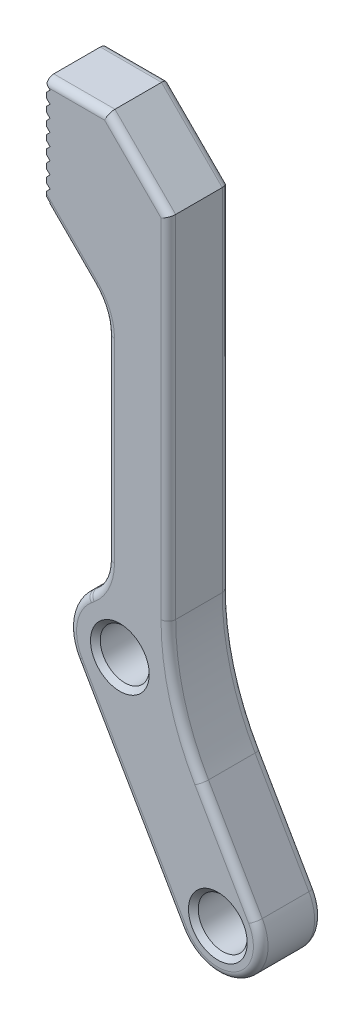
SolidWorks part; units mm, degrees
ref_plane "Ön Düzlem" through (0, 0, 0) normal (0, 0, 1) x (1, 0, 0)
ref_plane "Üst Düzlem" through (0, 0, 0) normal (0, 1, 0) x (1, 0, 0)
ref_plane "Sağ Düzlem" through (0, 0, 0) normal (1, 0, 0) x (0, 0, -1)
sketch "Çizim1" plane through (0, 0, 0) normal (0, 0, 1) x (1, 0, 0)
  line L0 (-37.3964, -419.0951) -> (-37.3964, 583.0751) construction
  line L1 (-37.3964, 12.3964) -> (-12.3964, 12.3964)
  line L2 (-12.3964, 12.3964) -> (12.3964, -12.3964)
  line L3 (12.3964, -12.3964) -> (12.3964, -182.3964)
  line L4 (12.3964, -182.3964) -> (47.7591, -243.6464)
  line L5 (17.4482, -261.1464) -> (-33.7917, -172.3964)
  line L6 (-33.7917, -172.3964) -> (-12.6036, -154.6175)
  line L7 (-12.6036, -154.6175) -> (-12.6036, -57.3964)
  line L8 (-12.6036, -57.3964) -> (-37.3964, -32.6036)
  line L9 (-37.3964, 12.3964) -> (-37.3964, -32.6036)
  line L10 (-37.3964, 10.3964) -> (-35.3964, 8.3964) construction
  line L11 (-35.3964, 8.3964) -> (-37.3964, 6.3964) construction
  arc A0 (17.4482, -261.1464) -> (47.7591, -243.6464) centre (32.6036, -252.3964) ccw
  circle A1 centre (-7.3964, -177.3964) radius 10
  circle A2 centre (32.6036, -252.3964) radius 10
  point P29 (0, 0)
  dimension "D1" = 35
  dimension "D18" = 20
  dimension "D19" = 20
  dimension "D2" = 100
  dimension "D3" = 45
  dimension "D4" = 135
  dimension "D5" = 25
  dimension "D6" = 25
  dimension "D7" = 170
  dimension "D8" = 70
  dimension "D9" = 80
  dimension "D10" = 4
  dimension "D11" = 4
  dimension "D12" = 26.3953
  dimension "D13" = 22.7789
  dimension "D14" = 30
  dimension "D15" = 24.7927
  dimension "D16" = 570.6787
  dimension "D17" = 246.6987
extrude "Yükseklik-Ekstrüzyon1" add sketch "Çizim1" along normal blind 25
fillet "Radyus1" radius 20 3 edges at (-12.6036, -57.3964, 12.5) (-12.6036, -154.6175, 12.5) (-33.7917, -172.3964, 12.5)
fillet "Radyus2" radius 100 1 edges at (12.3964, -182.3964, 12.5)
chamfer "Pah1" distance 2 angle 45 4 edges at (42.6036, -252.3964, 25) (42.6036, -252.3964, 0) (2.6036, -177.3964, 25) (2.6036, -177.3964, 0)
sketch "Çizim2" plane through (0, 0, 0) normal (0, 0, -1) x (-1, 0, 0)
  line L0 (37.3964, 12.3964) -> (37.3964, 10.3964)
  line L1 (37.3964, 12.3964) -> (37.3964, -32.6036) construction
  line L2 (37.3964, 10.3964) -> (35.8964, 8.8964)
  line L3 (35.8964, 8.8964) -> (37.3964, 7.3964)
  line L4 (37.3964, 7.3964) -> (37.3964, 5.3964)
  line L5 (37.3964, 5.3964) -> (35.8964, 3.8964)
  line L6 (35.8964, 3.8964) -> (37.3964, 2.3964)
  line L7 (37.3964, 2.3964) -> (37.3964, 0.3964)
  line L8 (37.3964, 0.3964) -> (35.8964, -1.1036)
  line L9 (35.8964, -1.1036) -> (37.3964, -2.6036)
  line L10 (37.3964, -2.6036) -> (37.3964, -4.6036)
  line L11 (37.3964, -4.6036) -> (35.8964, -6.1036)
  line L12 (35.8964, -6.1036) -> (37.3964, -7.6036)
  line L13 (37.3964, -7.6036) -> (37.3964, -9.6036)
  line L14 (37.3964, -9.6036) -> (35.8964, -11.1036)
  line L15 (35.8964, -11.1036) -> (37.3964, -12.6036)
  line L16 (37.3964, -12.6036) -> (37.3964, -14.6036)
  line L17 (37.3964, -14.6036) -> (35.8964, -16.1036)
  line L18 (35.8964, -16.1036) -> (37.3964, -17.6036)
  line L19 (37.3964, -17.6036) -> (37.3964, -19.6036)
  line L20 (37.3964, -19.6036) -> (35.8964, -21.1036)
  line L21 (35.8964, -21.1036) -> (37.3964, -22.6036)
  line L22 (37.3964, -22.6036) -> (37.3964, -24.6036)
  line L23 (37.3964, -24.6036) -> (35.8964, -26.1036)
  line L24 (35.8964, -26.1036) -> (37.3964, -27.6036)
  line L25 (37.3964, -27.6036) -> (37.3964, -29.6036)
  line L26 (37.3964, -29.6036) -> (35.8964, -31.1036)
  line L27 (35.8964, -31.1036) -> (37.3964, -32.6036)
  line L28 (37.3964, 12.3964) -> (40.9726, 12.3964)
  line L29 (40.9726, 12.3964) -> (40.9726, -32.6036)
  line L30 (40.9726, -32.6036) -> (37.3964, -32.6036)
  dimension "D1" = 3
  dimension "D2" = 2
  dimension "D3" = 9
extrude "Kes-Ekstrüzyon1" cut sketch "Çizim2" against normal through all both and the other way through all
fillet "Radyus3" radius 3 26 edges at (-27.9289, -42.0711, 25) (-14.126, -58.027, 25) (-12.6036, -105.486, 25) (-14.4775, -153.7437, 25) (-20.3419, -161.1107, 25) (-27.7763, -173.457, 25) (-3.9762, -224.0382, 25) (41.3536, -267.5518, 25) (36.7765, -224.6239, 25) (15.8038, -181.4834, 25) (-27.9289, -42.0711, 0) (-14.126, -58.027, 0) (-12.6036, -105.486, 0) (-14.4775, -153.7437, 0) (-20.3419, -161.1107, 0) (-27.7763, -173.457, 0) (-3.9762, -224.0382, 0) (41.3536, -267.5518, 0) (36.7765, -224.6239, 0) (15.8038, -181.4834, 0) (12.3964, -83.9989, 25) (0, 0, 25) (-24.8964, 12.3964, 25) (-24.8964, 12.3964, 0) (12.3964, -83.9989, 0) (0, 0, 0)
